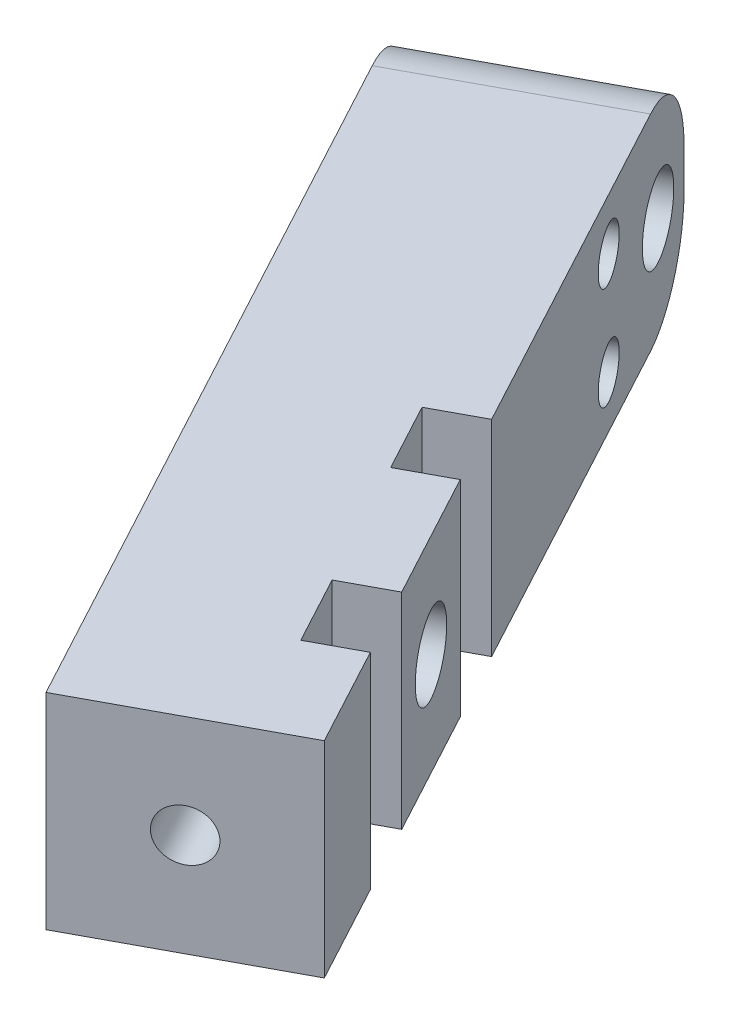
SolidWorks part; units mm, degrees
ref_plane "Front Plane" through (0, 0, 0) normal (0, 0, 1) x (1, 0, 0)
ref_plane "Top Plane" through (0, 0, 0) normal (0, 1, 0) x (1, 0, 0)
ref_plane "Right Plane" through (0, 0, 0) normal (1, 0, 0) x (0, 0, -1)
sketch "Sketch1" plane through (0, 0, 0) normal (0, 1, 0) x (1, 0, 0)
  line L0 (473.518, -385.0703) -> (212.9894, 99.3106)
  line L1 (212.9894, 99.3106) -> (-7.1837, -19.1115)
  line L2 (-7.1837, -19.1115) -> (-184.8169, 311.1482)
  line L3 (-184.8169, 311.1482) -> (35.3563, 429.5703)
  line L4 (35.3563, 429.5703) -> (-296.2256, 1046.0551)
  line L5 (-296.2256, 1046.0551) -> (-516.3987, 927.633)
  line L6 (-516.3987, 927.633) -> (-694.0318, 1257.8927)
  line L7 (-694.0318, 1257.8927) -> (-473.8587, 1376.3148)
  line L8 (-473.8587, 1376.3148) -> (-1416.4985, 3128.893)
  line L9 (473.518, -385.0703) -> (-407.1745, -858.7586)
  line L10 (-407.1745, -858.7586) -> (-2297.1911, 2655.2046)
  line L11 (-2297.1911, 2655.2046) -> (-1416.4985, 3128.893)
extrude "Boss-Extrude1" add sketch "Sketch1" along normal blind 1000
sketch "Sketch2" plane through (206.6285, 0, -111.137) normal (0.8807, 0, -0.4737) x (-0.4737, 0, -0.8807)
  line L0 (711.5715, 1000) -> (711.5715, 0) construction
  line L1 (361.5715, 1000) -> (1061.5715, 1000) construction
  line L2 (361.5715, 0) -> (1061.5715, 0) construction
  circle A0 centre (711.5715, 500) radius 187.5
  point P8 (0, 0)
extrude "Cut-Extrude2" cut sketch "Sketch2" against normal up to next
sketch "Sketch4" plane through (206.6285, 0, -111.137) normal (0.8807, 0, -0.4737) x (-0.4737, 0, -0.8807)
  line L0 (2431.5715, 1000) -> (2431.5715, 0) construction
  line L1 (1436.5715, 1000) -> (3426.5715, 1000) construction
  line L2 (1436.5715, 0) -> (3426.5715, 0) construction
  line L3 (-563.4285, 500) -> (3426.5715, 500) construction
  line L4 (-563.4285, 1000) -> (-563.4285, 0) construction
  line L5 (3426.5715, 1000) -> (3426.5715, 0) construction
sketch "Sketch5" plane through (-1623.127, 0, -3017.756) normal (-0.4737, 0, -0.8807) x (-0.8807, 0, 0.4737)
  line L1 (-234.6205, 0) -> (765.3795, 0)
  line L2 (-234.6205, 0) -> (-234.6205, 1000)
  line L3 (-234.6205, 1000) -> (765.3795, 1000)
  line L4 (765.3795, 0) -> (765.3795, 1000)
extrude "Boss-Extrude2" add sketch "Sketch5" along normal blind 310
fillet "Fillet1" radius 400 2 edges at (-2003.6882, 0, -3165.0635) (-2003.6882, 1000, -3165.0635)
sketch "Sketch6" plane through (206.6285, 0, -111.137) normal (0.8807, 0, -0.4737) x (-0.4737, 0, -0.8807)
  circle A0 centre (-1274.6828, 1852.9191) radius 281.8479
  circle A1 centre (-484.9707, 1893.7176) radius 469.7216
  circle A2 centre (3426.5715, 500) radius 187.5
extrude "Cut-Extrude3" cut sketch "Sketch6" against normal blind 650 contours A2
sketch "Sketch7" plane through (206.6285, 0, -111.137) normal (0.8807, 0, -0.4737) x (-0.4737, 0, -0.8807)
  line L0 (3736.5715, 600) -> (3736.5715, 400) construction
  line L1 (1436.5715, 1000) -> (3336.5715, 1000) construction
  line L2 (1436.5715, 0) -> (3336.5715, 0) construction
  circle A0 centre (2836.5715, 750) radius 125
  circle A1 centre (2836.5715, 250) radius 125
  point P6 (3736.5715, 500)
  dimension "D1" = 900
  dimension "D2" = 900
  dimension "D3" = 250
  dimension "D4" = 250
extrude "Cut-Extrude4" cut sketch "Sketch7" against normal up to next
sketch "Sketch8" plane through (266.8895, 0, 496.2073) normal (0.4737, 0, 0.8807) x (0.8807, 0, -0.4737)
  line L0 (-265.3795, 1000) -> (-265.3795, 0) construction
  line L1 (-765.3795, 1000) -> (234.6205, 1000) construction
  line L2 (-765.3795, 0) -> (234.6205, 0) construction
  circle A0 centre (-265.3795, 500) radius 125
extrude "Cut-Extrude5" cut sketch "Sketch8" against normal blind 700
